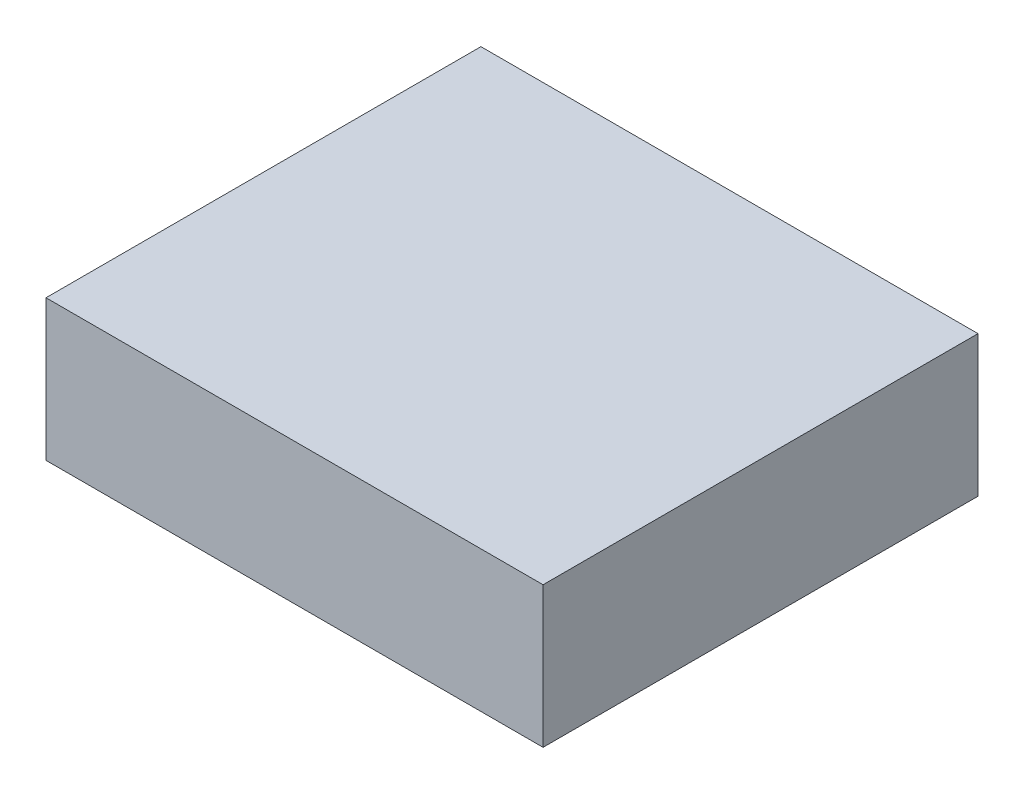
SolidWorks part; units mm, degrees
ref_plane "Front Plane" through (0, 0, 0) normal (0, 0, 1) x (1, 0, 0)
ref_plane "Top Plane" through (0, 0, 0) normal (0, 1, 0) x (1, 0, 0)
ref_plane "Right Plane" through (0, 0, 0) normal (1, 0, 0) x (0, 0, -1)
sketch "Sketch1" plane through (0, 0, 0) normal (0, 1, 0) x (1, 0, 0)
  line L1 (-24, 21) -> (24, 21)
  line L2 (-24, 21) -> (-24, -21)
  line L3 (-24, -21) -> (24, -21)
  line L4 (24, 21) -> (24, -21)
  line L5 (-24, 21) -> (24, -21) construction
  line L6 (-24, -21) -> (24, 21) construction
  point P0 (0, 0)
  dimension "D1" = 48
  dimension "D2" = 42
extrude "Boss-Extrude1" add sketch "Sketch1" along normal blind 13.6
